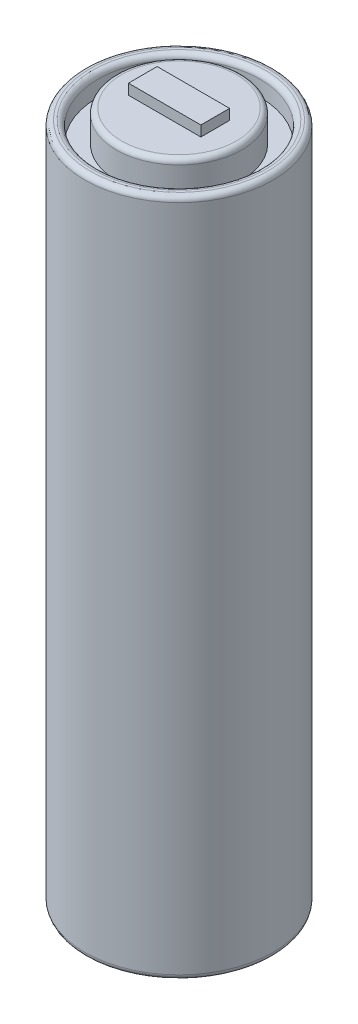
SolidWorks part; units mm, degrees
ref_plane "前视基准面" through (0, 0, 0) normal (0, 0, 1) x (1, 0, 0)
ref_plane "上视基准面" through (0, 0, 0) normal (0, 1, 0) x (1, 0, 0)
ref_plane "右视基准面" through (0, 0, 0) normal (1, 0, 0) x (0, 0, -1)
sketch "草图1" plane through (0, 0, 0) normal (0, 1, 0) x (1, 0, 0)
  circle A0 centre (0, 0) radius 9
  dimension "D1" = 18
extrude "凸台-拉伸1" add sketch "草图1" along normal blind 65
sketch "草图2" plane through (0, 65, 0) normal (0, 1, 0) x (1, 0, 0)
  circle A0 centre (0, 0) radius 7.75
  circle A1 centre (0, 0) radius 6
  dimension "D1" = 15.5
  dimension "D2" = 12
extrude "切除-拉伸1" cut sketch "草图2" against normal blind 2
sketch "草图4" plane through (0, 65, 0) normal (0, 1, 0) x (1, 0, 0)
  circle A0 centre (0, 0) radius 6 construction
  circle A1 centre (0, 0) radius 6
extrude "凸台-拉伸3" add sketch "草图4" along normal blind 1
sketch "草图3" plane through (0, 0, 0) normal (0, -1, 0) x (1, 0, 0)
  line L0 (-7.2242, 0) -> (6.1201, 0) construction
  line L1 (-3.4665, 1.3759) -> (3.4665, 1.3759)
  line L2 (-3.4665, 1.3759) -> (-3.4665, -1.3759)
  line L3 (-3.4665, -1.3759) -> (3.4665, -1.3759)
  line L4 (3.4665, 1.3759) -> (3.4665, -1.3759)
  line L5 (0, 2.7961) -> (0, -3.2399) construction
fillet "圆角1" radius 0.5 4 edges at (0, 65, 9) (0, 0, 9) (0, 65, 7.75) (0, 66, 6)
extrude "负焊接面" add sketch "草图3" along normal blind 1
sketch "草图5" plane through (0, 66, 0) normal (0, 1, 0) x (1, 0, 0)
  line L0 (-3.4665, 1.3759) -> (3.4665, 1.3759) construction
  line L1 (-3.4665, -1.3759) -> (-3.4665, 1.3759) construction
  line L2 (3.4665, -1.3759) -> (-3.4665, -1.3759) construction
  line L3 (3.4665, 1.3759) -> (3.4665, -1.3759) construction
  line L4 (-3.4665, 1.3759) -> (3.4665, 1.3759)
  line L5 (-3.4665, -1.3759) -> (-3.4665, 1.3759)
  line L6 (3.4665, -1.3759) -> (-3.4665, -1.3759)
  line L7 (3.4665, 1.3759) -> (3.4665, -1.3759)
extrude "正焊接面" add sketch "草图5" along normal blind 1
